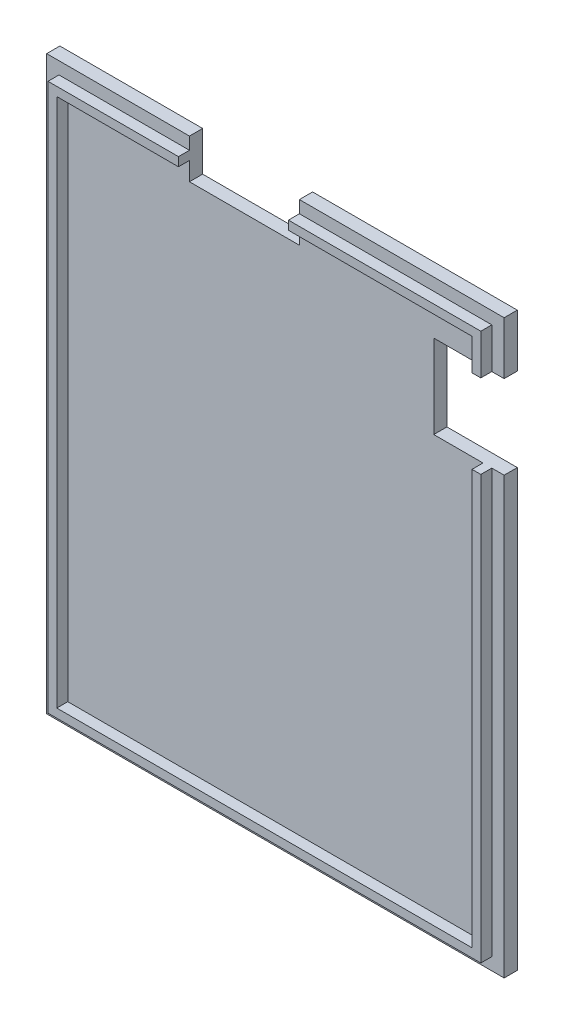
SolidWorks part; units mm, degrees
ref_plane "前基準面" through (0, 0, 0) normal (0, 0, 1) x (1, 0, 0)
ref_plane "上基準面" through (0, 0, 0) normal (0, 1, 0) x (1, 0, 0)
ref_plane "右基準面" through (0, 0, 0) normal (1, 0, 0) x (0, 0, -1)
sketch "草圖1" plane through (0, 0, 0) normal (0, 0, 1) x (1, 0, 0)
  line L1 (-52, 65) -> (52, 65)
  line L2 (-52, 65) -> (-52, -65)
  line L3 (-52, -65) -> (52, -65)
  line L4 (52, 65) -> (52, -65)
  line L5 (-52, 65) -> (52, -65) construction
  line L6 (-52, -65) -> (52, 65) construction
  point P0 (0, 0)
  dimension "D1" = 104
  dimension "D2" = 130
extrude "填料-伸長1" add sketch "草圖1" along normal blind 3
sketch "草圖2" plane through (0, 0, 3) normal (0, 0, 1) x (1, 0, 0)
  line L4 (47.2, -60.2) -> (47.2, 60.2)
  line L5 (47.2, 60.2) -> (-47.2, 60.2)
  line L6 (-47.2, 60.2) -> (-47.2, -60.2)
  line L7 (-47.2, -60.2) -> (47.2, -60.2)
  line L8 (49.2, -62.2) -> (49.2, 62.2)
  line L9 (49.2, 62.2) -> (-49.2, 62.2)
  line L10 (-49.2, 62.2) -> (-49.2, -62.2)
  line L11 (-49.2, -62.2) -> (49.2, -62.2)
  line L12 (49.2, -62.2) -> (49.2, 62.2)
  line L13 (49.2, 62.2) -> (-49.2, 62.2)
  line L14 (-49.2, 62.2) -> (-49.2, -62.2)
  line L15 (-49.2, -62.2) -> (49.2, -62.2)
  dimension "D1" = 2.8
  dimension "D2" = 2
extrude "填料-伸長2" add sketch "草圖2" along normal blind 2.5 contours L14 L15 L12 L13 L7 L6 L5 L4
sketch "草圖3" plane through (0, 0, 0) normal (0, 0, -1) x (-1, 0, 0)
  line L0 (-52, -65) -> (-52, 65) construction
  line L1 (-52, 53) -> (-36, 53)
  line L2 (-52, 53) -> (-52, 34)
  line L3 (-52, 34) -> (-36, 34)
  line L4 (-36, 53) -> (-36, 34)
  line L5 (-52, 65) -> (52, 65) construction
  line L6 (-5.4588, 65) -> (19.5412, 65)
  line L8 (-5.4588, 65) -> (-5.4588, 56)
  line L9 (-5.4588, 56) -> (19.5412, 56)
  line L10 (19.5412, 65) -> (19.5412, 56)
  point P8 (0, 65)
  point P10 (0, 0)
  point P12 (0, 0)
  dimension "D1" = 12
  dimension "D2" = 19
  dimension "D3" = 16
  dimension "D4" = 9
  dimension "D5" = 25
extrude "除料-伸長1" cut sketch "草圖3" against normal through all
